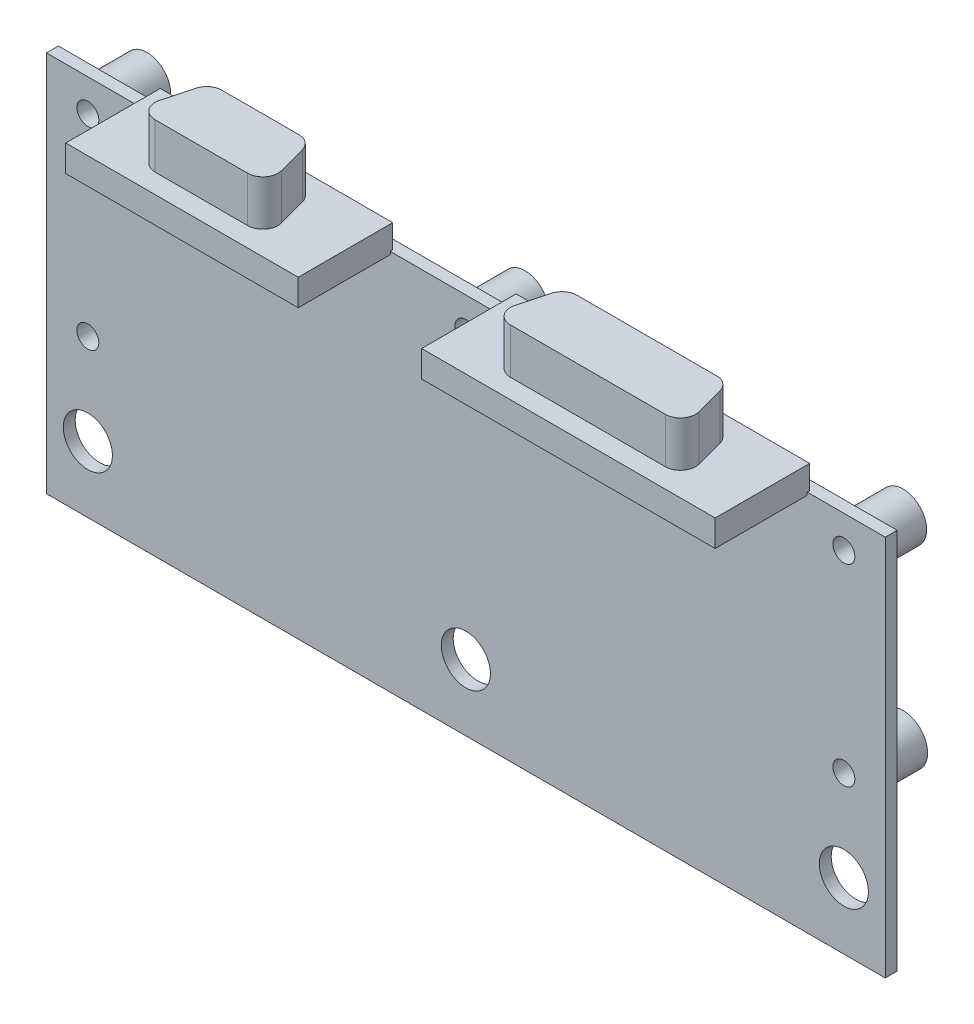
SolidWorks part; units mm, degrees
ref_plane "front" through (0, 0, 0) normal (0, 0, 1) x (1, 0, 0)
ref_plane "top" through (0, 0, 0) normal (0, 1, 0) x (1, 0, 0)
ref_plane "right" through (0, 0, 0) normal (1, 0, 0) x (0, 0, -1)
ref_plane "Plane1" through (0, 0, 6.35) normal (0, 0, 1) x (1, 0, 0)
sketch "Sketch1" plane through (0, 0, 6.35) normal (0, 0, 1) x (1, 0, 0)
  line L1 (-56.3626, -51.308) -> (56.3626, -51.308)
  line L2 (-56.3626, -51.308) -> (-56.3626, 0)
  line L3 (-56.3626, 0) -> (56.3626, 0)
  line L4 (56.3626, -51.308) -> (56.3626, 0)
  dimension "D1" = 112.7252
  dimension "D2" = 51.308
extrude "Extrude1" add sketch "Sketch1" along normal blind 1.6002
sketch "Sketch2" plane through (0, 0, 0) normal (0, 0, 1) x (1, 0, 0)
  line L0 (56.3626, 0) -> (-56.3626, 0) construction
  circle A0 centre (-50.8, -42.418) radius 3.302 construction
  circle A1 centre (-50.8, -4.318) radius 3.175
  circle A2 centre (50.8, -4.318) radius 3.175
  circle A3 centre (50.8, -42.418) radius 3.302 construction
  circle A4 centre (-50.8, -30.226) radius 3.302
  circle A5 centre (0, -42.418) radius 3.302 construction
  circle A6 centre (50.8, -30.226) radius 3.302
  circle A7 centre (0, -4.318) radius 3.175
  dimension "D1" = 6.604
  dimension "D2" = 6.35
  dimension "D8" = 1.143
  dimension "D3" = 50.8
  dimension "D4" = 50.8
  dimension "D5" = 38.1
  dimension "D6" = 25.908
  dimension "D7" = 4.318
extrude "Extrude2" add sketch "Sketch2" along normal up to next
sketch "Sketch3" plane through (0, 0, 0) normal (0, 0, 1) x (1, 0, 0)
  circle A0 centre (50.8, -42.418) radius 3.302 construction
  circle A1 centre (0, -42.418) radius 3.302 construction
  circle A2 centre (-50.8, -42.418) radius 3.302 construction
  circle A3 centre (50.8, -42.418) radius 3.302
  circle A4 centre (0, -42.418) radius 3.302
  circle A5 centre (-50.8, -42.418) radius 3.302
  circle A6 centre (50.8, -30.226) radius 1.4732
  circle A7 centre (50.8, -4.318) radius 1.4732
  circle A8 centre (0, -4.318) radius 1.4732
  circle A9 centre (-50.8, -4.318) radius 1.4732
  circle A10 centre (-50.8, -30.226) radius 1.4732
  dimension "D1" = 2.9464
extrude "Cut-Extrude1" cut sketch "Sketch3" along normal blind 12.7
ref_plane "Plane2" through (0, 3.175, 0) normal (0, 1, 0) x (-1, 0, 0)
sketch "Sketch4" plane through (0, 3.175, 0) normal (0, 1, 0) x (-1, 0, 0)
  line L1 (41.402, 7.62) -> (10.16, 7.62)
  line L2 (41.402, 7.62) -> (41.402, 20.32)
  line L3 (41.402, 20.32) -> (10.16, 20.32)
  line L4 (10.16, 7.62) -> (10.16, 20.32)
  line L5 (-6.4262, 7.62) -> (-45.8724, 7.62)
  line L6 (-6.4262, 7.62) -> (-6.4262, 20.32)
  line L7 (-6.4262, 20.32) -> (-45.8724, 20.32)
  line L8 (-45.8724, 7.62) -> (-45.8724, 20.32)
  dimension "D1" = 7.62
  dimension "D2" = 12.7
  dimension "D3" = 39.4462
  dimension "D4" = 31.242
  dimension "D5" = 10.16
  dimension "D6" = 6.4262
extrude "Extrude3" add sketch "Sketch4" against normal blind 3.556
sketch "Sketch5" plane through (0, 3.175, 0) normal (0, 1, 0) x (1, 0, 0)
  line L0 (15.7353, -17.7038) -> (36.5633, -17.7038)
  line L1 (38.5261, -15.1459) -> (37.4916, -11.2851)
  line L2 (35.5288, -9.779) -> (16.7698, -9.779)
  line L3 (26.1493, -7.62) -> (26.1493, 3.8318) construction
  line L4 (6.4262, -7.62) -> (45.8724, -7.62) construction
  line L5 (-25.781, -7.62) -> (-25.781, 2.2991) construction
  line L6 (-41.402, -7.62) -> (-10.16, -7.62) construction
  line L7 (-30.9695, -9.779) -> (-20.5925, -9.779)
  line L8 (-18.6297, -11.2851) -> (-17.5952, -15.1459)
  line L9 (-19.558, -17.7038) -> (-32.004, -17.7038)
  line L10 (-32.9323, -11.2851) -> (-33.9668, -15.1459)
  line L11 (13.7725, -15.1459) -> (14.807, -11.2851)
  arc A0 (36.5633, -17.7038) -> (38.5261, -15.1459) centre (36.5633, -15.6718) ccw
  arc A1 (37.4916, -11.2851) -> (35.5288, -9.779) centre (35.5288, -11.811) ccw
  arc A2 (-17.5952, -15.1459) -> (-19.558, -17.7038) centre (-19.558, -15.6718) cw
  arc A3 (-20.5925, -9.779) -> (-18.6297, -11.2851) centre (-20.5925, -11.811) cw
  arc A4 (-33.9668, -15.1459) -> (-32.004, -17.7038) centre (-32.004, -15.6718) ccw
  arc A5 (-30.9695, -9.779) -> (-32.9323, -11.2851) centre (-30.9695, -11.811) ccw
  arc A6 (15.7353, -17.7038) -> (13.7725, -15.1459) centre (15.7353, -15.6718) cw
  arc A7 (14.807, -11.2851) -> (16.7698, -9.779) centre (16.7698, -11.811) cw
  dimension "D4" = 2.032
  dimension "D6" = 2.032
  dimension "D1" = 2.159
  dimension "D2" = 7.9248
  dimension "D3" = 75
  dimension "D5" = 24.892
  dimension "D7" = 16.51
extrude "Extrude4" add sketch "Sketch5" along normal blind 6.096
